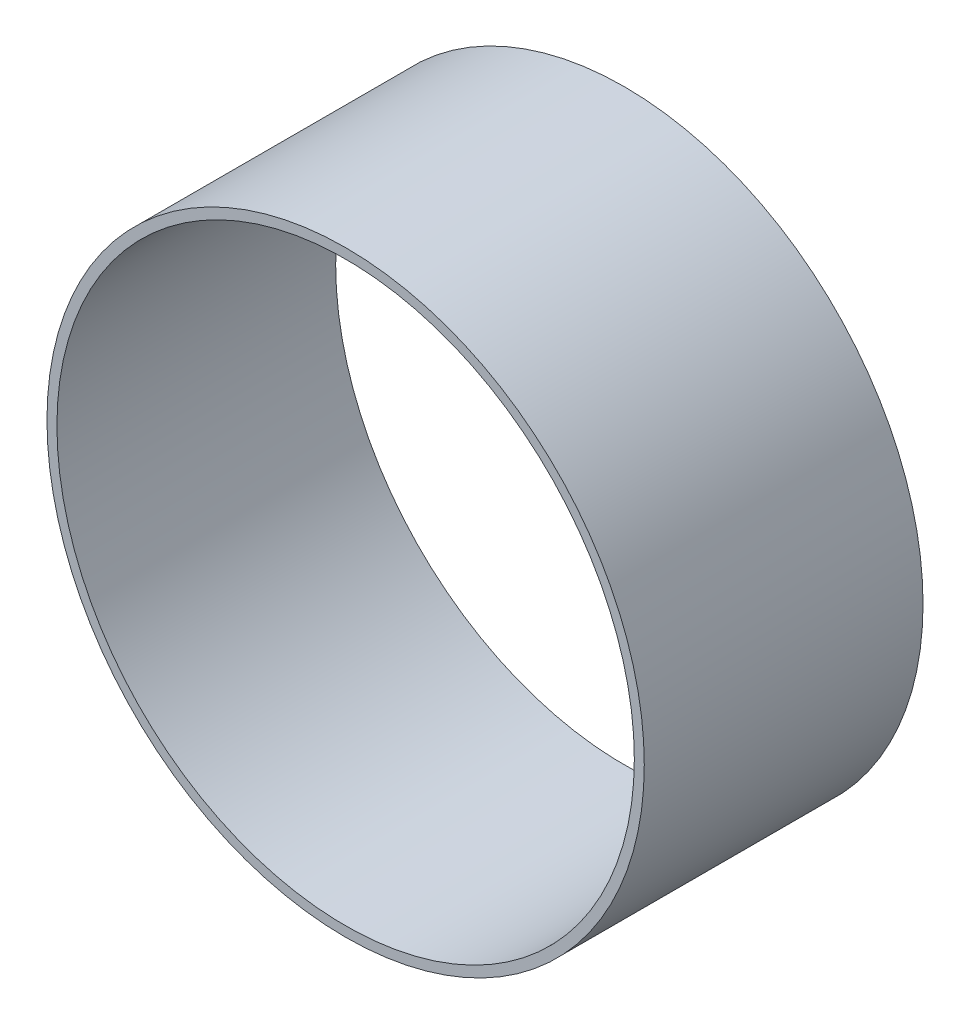
SolidWorks part; units mm, degrees
ref_plane "Plan de face" through (0, 0, 0) normal (0, 0, 1) x (1, 0, 0)
ref_plane "Plan de dessus" through (0, 0, 0) normal (0, 1, 0) x (1, 0, 0)
ref_plane "Plan de droite" through (0, 0, 0) normal (1, 0, 0) x (0, 0, -1)
sketch "Esquisse1" plane through (0, 0, 0) normal (0, 0, 1) x (1, 0, 0)
  circle A0 centre (0, 0) radius 29
  circle A1 centre (0, 0) radius 30
extrude "Boss.-Extru.1" add sketch "Esquisse1" along normal blind 28
